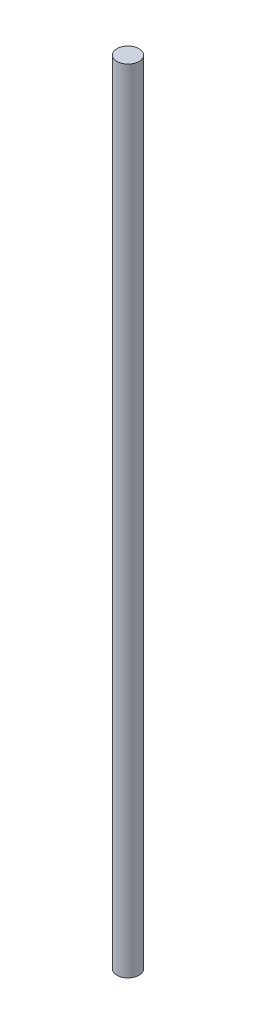
SolidWorks part; units mm, degrees
material "1.2343 (X38CrMoV5-1)"
ref_plane "Front Plane" through (0, 0, 0) normal (0, 0, 1) x (1, 0, 0)
ref_plane "Top Plane" through (0, 0, 0) normal (0, 1, 0) x (1, 0, 0)
ref_plane "Right Plane" through (0, 0, 0) normal (1, 0, 0) x (0, 0, -1)
sketch "Sketch1" plane through (0, 0, 0) normal (0, 1, 0) x (1, 0, 0)
  circle A0 centre (0, 0) radius 5
  dimension "D1" = 10
extrude "Boss-Extrude1" add sketch "Sketch1" along normal blind 357.66
